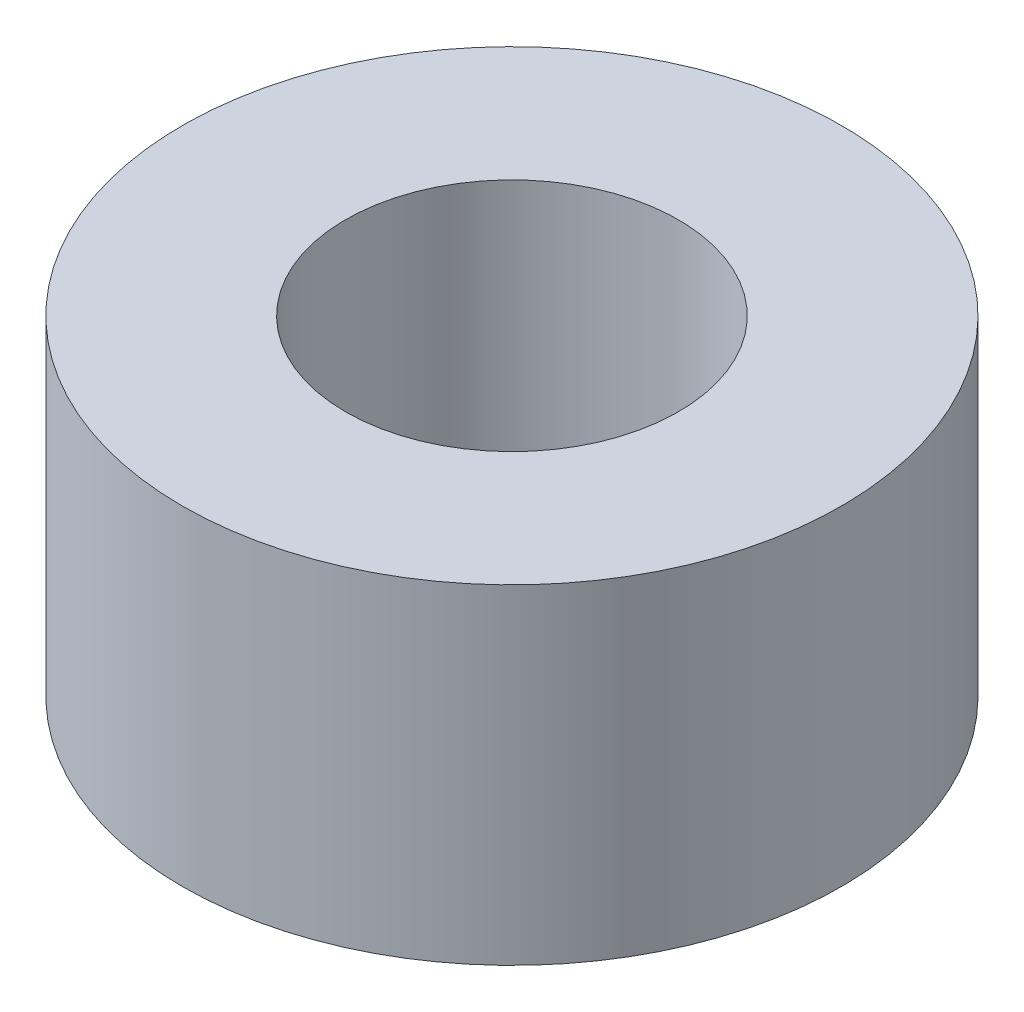
SolidWorks part; units mm, degrees
ref_plane "正面" through (0, 0, 0) normal (0, 0, 1) x (1, 0, 0)
ref_plane "平面" through (0, 0, 0) normal (0, 1, 0) x (1, 0, 0)
ref_plane "右側面" through (0, 0, 0) normal (1, 0, 0) x (0, 0, -1)
sketch "ｽｹｯﾁ1" plane through (0, 0, 0) normal (0, 1, 0) x (1, 0, 0)
  circle A0 centre (0, 0) radius 2.525
  circle A1 centre (0, 0) radius 5
  dimension "D1" = 5.05
  dimension "D2" = 10
extrude "ﾎﾞｽ - 押し出し1" add sketch "ｽｹｯﾁ1" along normal mid plane 5
